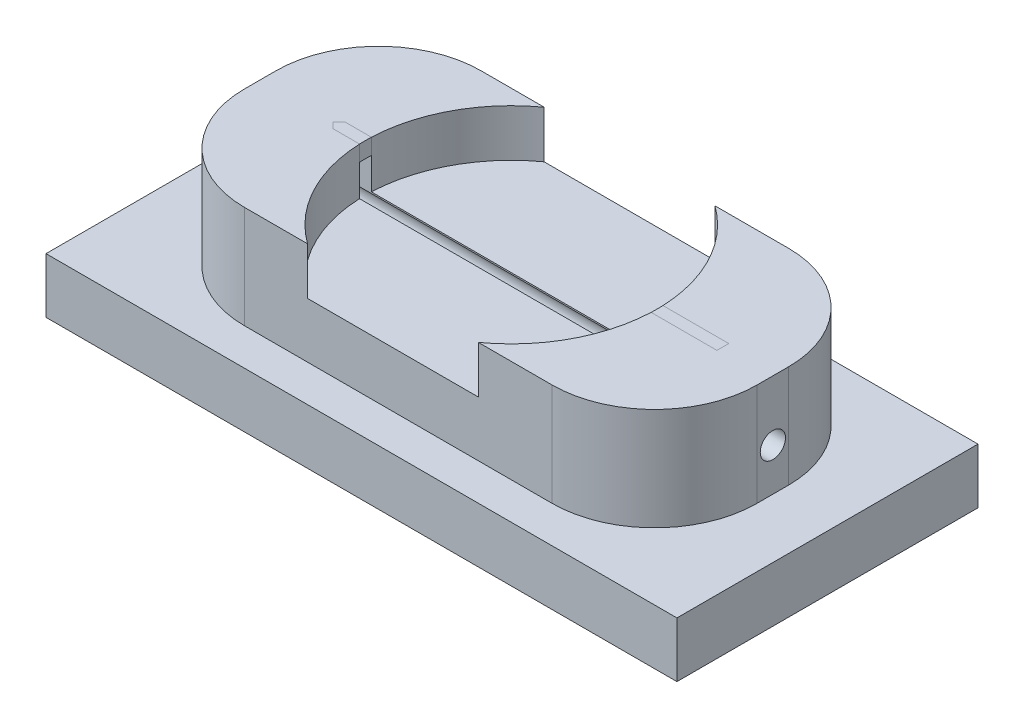
SolidWorks part; units mm, degrees
ref_plane "Front Plane" through (0, 0, 0) normal (0, 0, 1) x (1, 0, 0)
ref_plane "Top Plane" through (0, 0, 0) normal (0, 1, 0) x (1, 0, 0)
ref_plane "Right Plane" through (0, 0, 0) normal (1, 0, 0) x (0, 0, -1)
sketch "Sketch1" plane through (0, 0, 0) normal (0, 1, 0) x (1, 0, 0)
  line L1 (-25, -15) -> (40, -15)
  line L2 (-25, -15) -> (-25, 15)
  line L3 (-25, 15) -> (40, 15)
  line L4 (40, -15) -> (40, 15)
  line L5 (-25, -15) -> (40, 15) construction
  line L6 (-25, 15) -> (40, -15) construction
  point P0 (0, 0)
  dimension "D1" = 30
  dimension "D2" = 65
extrude "Boss-Extrude1" add sketch "Sketch1" along normal blind 58
sketch "Sketch2" plane through (0, 58, 0) normal (0, 1, 0) x (1, 0, 0)
  line L0 (-15, 0.75) -> (15, 0.75)
  line L3 (15, -0.75) -> (-15, -0.75)
  line L4 (-15, -0.75) -> (-15.75, 0)
  line L5 (-15.75, 0) -> (-15, 0.75)
  line L6 (15, 0.75) -> (33.657, 0.75)
  line L7 (33.657, 0.75) -> (33.657, -0.75)
  line L8 (33.657, -0.75) -> (15, -0.75)
  dimension "D1" = 15
  dimension "D2" = 15
  dimension "D3" = 15
  dimension "D4" = 15
  dimension "D5" = 0.75
  dimension "D6" = 0.75
extrude "Cut-Extrude1" cut sketch "Sketch2" against normal blind 70
sketch "Sketch3" plane through (-25, 0, 0) normal (-1, 0, 0) x (0, 0, 1)
  line L0 (-15, 58) -> (15, 58) construction
  circle A0 centre (0, 50.4) radius 1.6
  dimension "D1" = 3.2
  dimension "D2" = 7.6
extrude "Cut-Extrude2" cut sketch "Sketch3" against normal through all and the other way through all
fillet "Fillet1" radius 13 4 edges at (40, 29, -15) (-25, 29, -15) (40, 29, 15) (-25, 29, 15)
ref_plane "Plane2" through (0, -10, 0) normal (0, -1, 0) x (-1, 0, 0)
sketch "Sketch15" plane through (0, -10, 0) normal (0, -1, 0) x (-1, 0, 0)
  line L1 (-41.9055, 15.8797) -> (41.7906, 15.8797)
  line L2 (-41.9055, 15.8797) -> (-41.9055, -15.8187)
  line L3 (-41.9055, -15.8187) -> (41.7906, -15.8187)
  line L4 (41.7906, 15.8797) -> (41.7906, -15.8187)
extrude "Cut-Extrude7" cut sketch "Sketch15" against normal blind 50
ref_plane "Plane3" through (0, 40, 0) normal (0, -1, 0) x (-1, 0, 0)
sketch "Sketch16" plane through (0, 40, 0) normal (0, -1, 0) x (-1, 0, 0)
  line L0 (-40, 2) -> (-40, -2) construction
  line L1 (-47.5, 18.511) -> (32.5, 18.511)
  line L2 (-47.5, 18.511) -> (-47.5, -19.6628)
  line L3 (-47.5, -19.6628) -> (32.5, -19.6628)
  line L4 (32.5, 18.511) -> (32.5, -19.6628)
  line L5 (25, -2) -> (25, 2) construction
  dimension "D1" = 80
  dimension "D2" = 7.5
  dimension "D3" = 7.5
extrude "Boss-Extrude4" add sketch "Sketch16" along normal blind 2 and the other way blind 5
ref_plane "Plane4" through (0, 58, 0) normal (0, 1, 0) x (1, 0, 0)
sketch "Sketch18" plane through (0, 58, 0) normal (0, 1, 0) x (1, 0, 0)
  circle A0 centre (6.8285, 0) radius 18.5
  dimension "D1" = 37
sketch "Sketch19" plane through (0, 58, 0) normal (0, 1, 0) x (1, 0, 0)
  line L0 (33.657, 0.75) -> (-15, 0.75) construction
  line L1 (-15, -0.75) -> (33.657, -0.75) construction
  line L2 (-11.6563, 0.75) -> (-15, 0.75)
  line L3 (-15, 0.75) -> (-15.75, 0)
  line L4 (-15.75, 0) -> (-15, -0.75)
  line L5 (-15, -0.75) -> (-11.6563, -0.75)
  line L6 (-15, -0.75) -> (33.657, -0.75) construction
  line L7 (25.3133, 0.75) -> (33.657, 0.75)
  line L8 (33.657, 0.75) -> (33.657, -0.75)
  line L9 (33.657, -0.75) -> (25.3133, -0.75)
  arc A0 (-11.6563, 0.75) -> (-11.6563, -0.75) centre (6.8285, 0) ccw
  circle A1 centre (6.8285, 0) radius 18.5 construction
  arc A2 (25.3133, 0.75) -> (25.3133, -0.75) centre (6.8285, 0) cw
extrude "Cut-Extrude8" cut sketch "Sketch18" against normal blind 6 contours A0
extrude "Boss-Extrude5" add sketch "Sketch19" against normal blind 2 separate body
